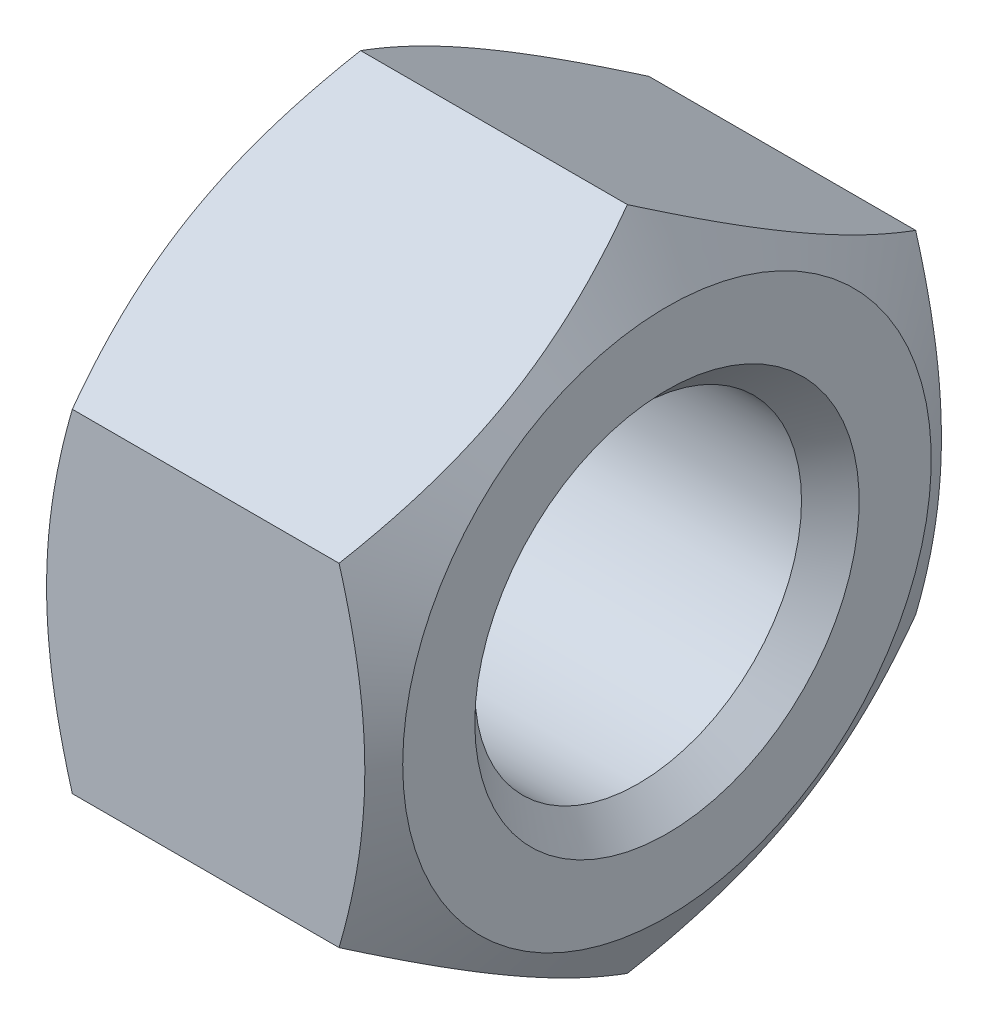
SolidWorks part; units mm, degrees
ref_plane "Спереди" through (0, 0, 0) normal (0, 0, 1) x (1, 0, 0)
ref_plane "Сверху" through (0, 0, 0) normal (0, 1, 0) x (1, 0, 0)
ref_plane "Справа" through (0, 0, 0) normal (1, 0, 0) x (0, 0, -1)
sketch "Эскиз1" plane through (0, 0, 0) normal (0, 0, 1) x (1, 0, 0)
  line L0 (0.9, 5.1) -> (9.9, 5.1)
  line L1 (10.8, 6) -> (10.8, 8.25)
  line L2 (10.8, 8.25) -> (9.3278, 10.8)
  line L3 (9.3278, 10.8) -> (1.4722, 10.8)
  line L4 (1.4722, 10.8) -> (0, 8.25)
  line L5 (0, 8.25) -> (0, 6)
  line L6 (0, 6) -> (0.9, 5.1)
  line L7 (10.8, 6) -> (9.9, 5.1)
  line L8 (0, 0) -> (1.4563, 0) construction
  dimension "D1" = 135
  dimension "D2" = 120
  dimension "D3" = 120
  dimension "D4" = 135
  dimension "e" = 21.6
  dimension "m" = 10.8
  dimension "Dw" = 16.5
  dimension "Da" = 12
  dimension "D" = 10.2
revolve "Повернуть1" add sketch "Эскиз1" angle 360 about L8
sketch "Эскиз2" plane through (0, 0, 0) normal (-1, 0, 0) x (0, 0, 1)
  line L1 (0, 10.3923) -> (-9, 5.1962)
  line L2 (-9, 5.1962) -> (-9, -5.1962)
  line L3 (-9, -5.1962) -> (0, -10.3923)
  line L4 (0, -10.3923) -> (9, -5.1962)
  line L5 (9, -5.1962) -> (9, 5.1962)
  line L6 (9, 5.1962) -> (0, 10.3923)
  circle A0 centre (0, 0) radius 9 construction
  dimension "S" = 18
extrude "Вырез-Вытянуть1" cut sketch "Эскиз2" against normal through all flip side to cut
